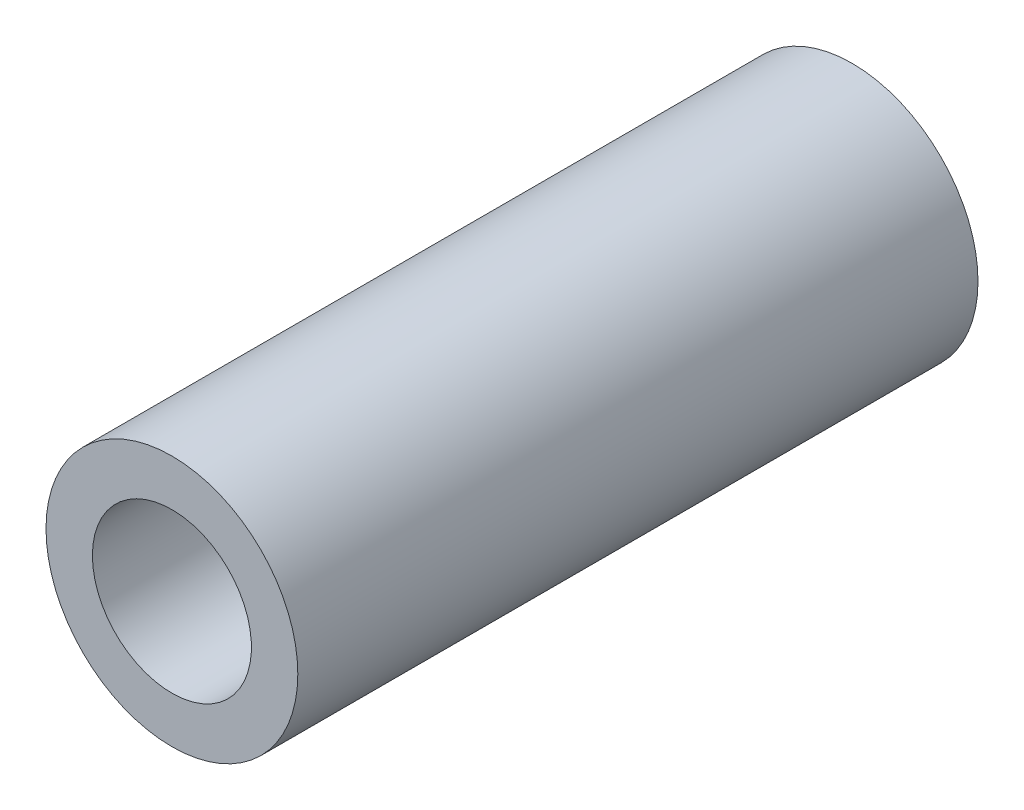
SolidWorks part; units mm, degrees
ref_plane "Front Plane" through (0, 0, 0) normal (0, 0, 1) x (1, 0, 0)
ref_plane "Top Plane" through (0, 0, 0) normal (0, 1, 0) x (1, 0, 0)
ref_plane "Right Plane" through (0, 0, 0) normal (1, 0, 0) x (0, 0, -1)
sketch "Sketch1" plane through (0, 0, 0) normal (0, 0, 1) x (1, 0, 0)
  circle A0 centre (0, 0) radius 2.375
  circle A1 centre (0, 0) radius 1.5
  dimension "OD" = 4.75
  dimension "ID" = 3
extrude "Extrude1" add sketch "Sketch1" along normal mid plane 12.83
sketch "Sketch2" plane through (0, 0, 0) normal (1, 0, 0) x (0, 0, -1)
  line L0 (-6.415, -1.5) -> (6.415, -1.5) construction
  line L3 (6.415, 1.5) -> (-6.415, 1.5) construction
  line L5 (-6.415, -1.5) -> (6.415, -1.5)
  line L6 (6.415, 1.5) -> (-6.415, 1.5)
sketch "Sketch4" plane through (0, 0, 6.415) normal (0, 0, 1) x (1, 0, 0)
  line L0 (0, 0) -> (-1.0607, 1.0607)
  line L1 (0, -55) -> (0, 55) construction
  circle A0 centre (0, 0) radius 1.5 construction
  dimension "D1" = 45
